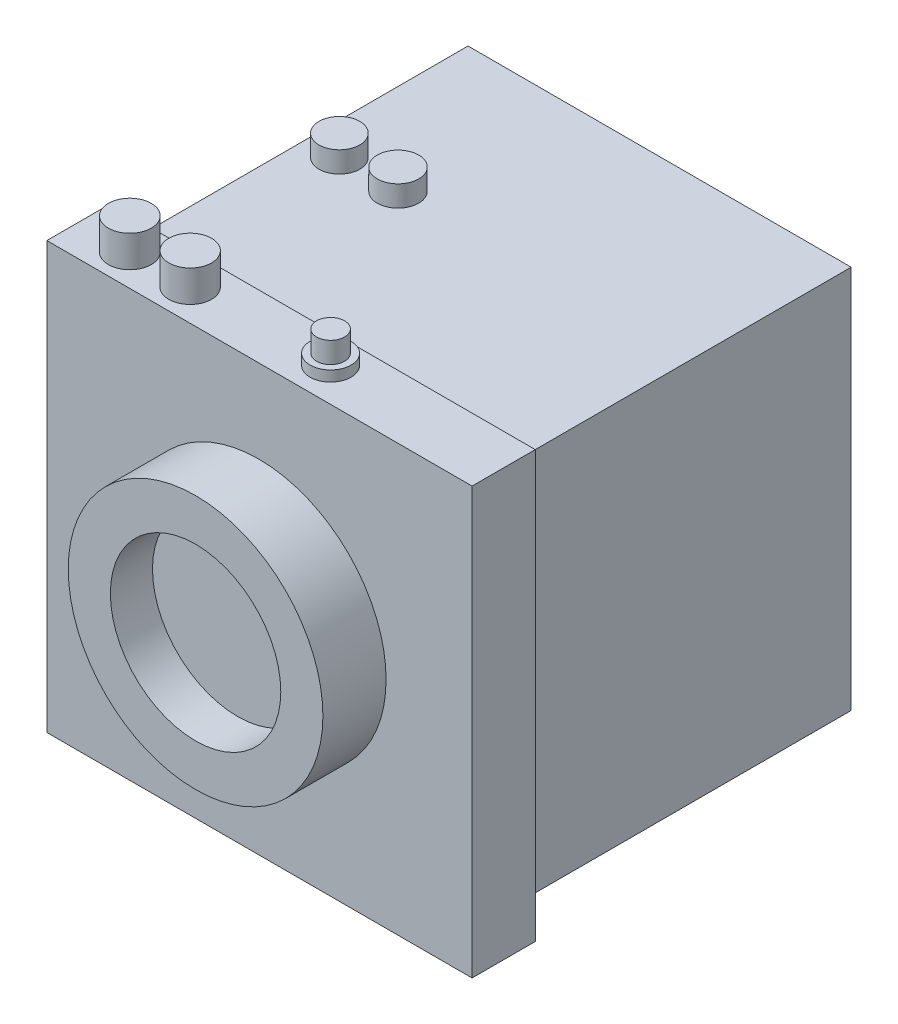
SolidWorks part; units mm, degrees
ref_plane "Front Plane" through (0, 0, 0) normal (0, 0, 1) x (1, 0, 0)
ref_plane "Top Plane" through (0, 0, 0) normal (0, 1, 0) x (1, 0, 0)
ref_plane "Right Plane" through (0, 0, 0) normal (1, 0, 0) x (0, 0, -1)
sketch "Sketch1" plane through (0, 0, 0) normal (0, 0, 1) x (1, 0, 0)
  line L1 (-30.1494, 28.1842) -> (21.1382, 28.1842)
  line L2 (-30.1494, 28.1842) -> (-30.1494, -23.1992)
  line L3 (-30.1494, -23.1992) -> (21.1382, -23.1992)
  line L4 (21.1382, 28.1842) -> (21.1382, -23.1992)
  dimension "D1" = 51.2876
  dimension "D2" = 51.3835
extrude "Boss-Extrude1" add sketch "Sketch1" along normal blind 7.62
shell "Shell2" thickness 2.54
sketch "Sketch2" plane through (0, 0, 0) normal (0, 0, 1) x (1, 0, 0)
  line L0 (18.5982, 25.6442) -> (-27.6094, 25.6442) construction
  line L1 (18.5982, 25.6442) -> (-27.6094, 25.6442)
  line L2 (18.5982, 25.6442) -> (18.5982, -20.6592)
  line L3 (18.5982, -20.6592) -> (-27.6094, -20.6592)
  line L4 (-27.6094, 25.6442) -> (-27.6094, -20.6592)
  line L5 (18.5982, -20.6592) -> (18.5982, 25.6442) construction
sketch "Sketch3" plane through (0, 0, 5.08) normal (0, 0, -1) x (-1, 0, 0)
  line L1 (-18.5982, 25.6442) -> (27.6094, 25.6442)
  line L2 (-18.5982, 25.6442) -> (-18.5982, -20.6592)
  line L3 (-18.5982, -20.6592) -> (27.6094, -20.6592)
  line L4 (27.6094, 25.6442) -> (27.6094, -20.6592)
extrude "Boss-Extrude2" add sketch "Sketch3" along normal blind 45.72 separate body
sketch "Sketch8" plane through (0, 0, 7.62) normal (0, 0, 1) x (1, 0, 0)
  line L0 (21.1382, 28.1842) -> (-30.1494, 28.1842) construction
  circle A0 centre (-4.591, 2.7842) radius 15.3566
  dimension "D1" = 25.4
extrude "Boss-Extrude4" add sketch "Sketch8" along normal blind 7.62
shell "Shell9" thickness 5.08
sketch "Sketch11" plane through (0, 28.1842, 0) normal (0, 1, 0) x (1, 0, 0)
  circle A0 centre (-23.9248, -3.8352) radius 2.5898
  circle A1 centre (-16.6467, -3.8352) radius 2.5766
  dimension "D1" = 5.1533
  dimension "D2" = 5.1795
extrude "Boss-Extrude5" add sketch "Sketch11" along normal blind 3.81
sketch "Sketch12" plane through (0, 28.1842, 0) normal (0, 1, 0) x (1, 0, 0)
  circle A0 centre (0, -3.5465) radius 2.4749
extrude "Boss-Extrude6" add sketch "Sketch12" along normal blind 1.27
sketch "Sketch13" plane through (0, 29.4542, 0) normal (0, 1, 0) x (1, 0, 0)
  circle A0 centre (0, -3.5465) radius 1.689
extrude "Boss-Extrude7" add sketch "Sketch13" along normal blind 2.54
sketch "Sketch16" plane through (0, 25.6442, 0) normal (0, 1, 0) x (1, 0, 0)
  circle A0 centre (-16.659, 21.2409) radius 2.4967
  circle A1 centre (-23.7266, 21.2409) radius 2.4628
  dimension "D1" = 4.9256
  dimension "D2" = 4.9934
extrude "Boss-Extrude9" add sketch "Sketch16" along normal blind 2.54
